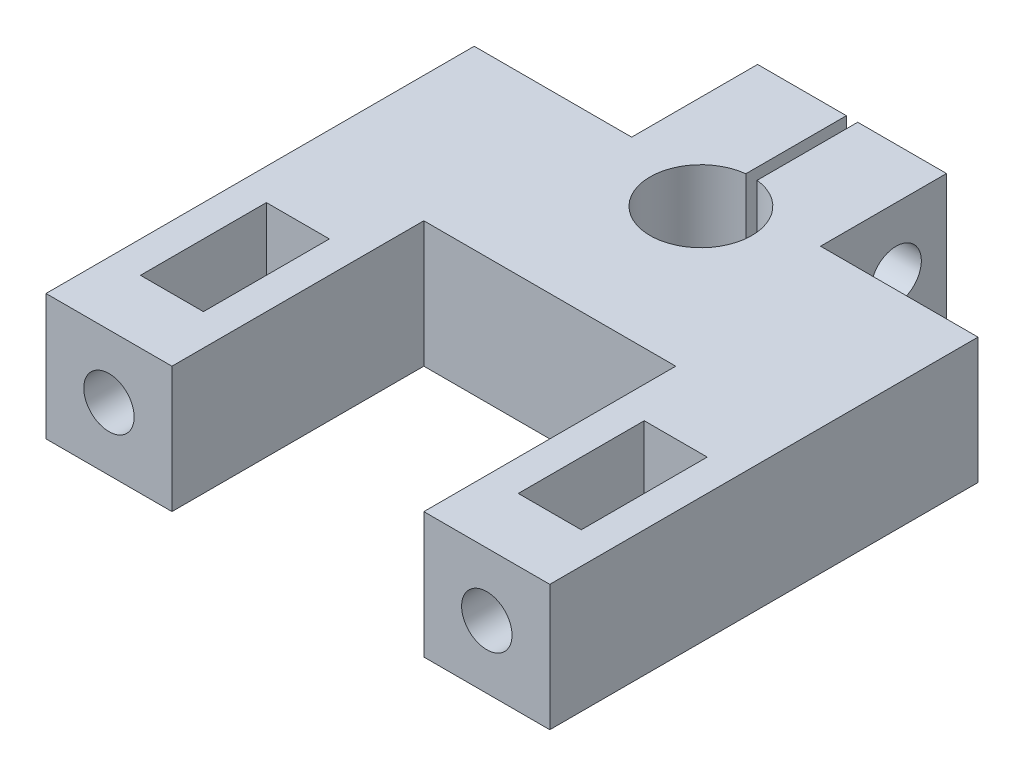
SolidWorks part; units mm, degrees
ref_plane "Front Plane" through (0, 0, 0) normal (0, 0, 1) x (1, 0, 0)
ref_plane "Top Plane" through (0, 0, 0) normal (0, 1, 0) x (1, 0, 0)
ref_plane "Right Plane" through (0, 0, 0) normal (1, 0, 0) x (0, 0, -1)
sketch "Sketch1" plane through (0, 0, 0) normal (0, 1, 0) x (1, 0, 0)
  line L0 (-20, -10) -> (-20, 20)
  line L1 (-20, 20) -> (20, 20)
  line L2 (-10, -10) -> (-10, 10)
  line L3 (-10, 10) -> (10, 10)
  line L4 (10, -10) -> (10, 10)
  line L5 (-10, -10) -> (10, 10) construction
  line L6 (-10, 10) -> (10, -10) construction
  line L7 (20, -10) -> (20, 20)
  line L8 (-20, -10) -> (-10, -10)
  line L9 (10, -10) -> (20, -10)
  point P0 (0, 0)
  dimension "D1" = 20
  dimension "D2" = 10
extrude "Boss-Extrude1" add sketch "Sketch1" along normal blind 10
sketch "Sketch2" plane through (0, 0, 10) normal (0, 0, 1) x (1, 0, 0)
  line L0 (-20, 5) -> (-10, 5) construction
  line L1 (-20, 10) -> (-20, 0) construction
  line L2 (-10, 10) -> (-10, 0) construction
  line L5 (10, 5) -> (20, 5) construction
  line L6 (10, 10) -> (10, 0) construction
  line L7 (20, 10) -> (20, 0) construction
  circle A0 centre (-15, 5) radius 2
  circle A1 centre (15, 5) radius 2
  dimension "D1" = 4
extrude "Cut-Extrude1" cut sketch "Sketch2" against normal blind 15
sketch "Sketch3" plane through (0, 0, -10) normal (0, 0, 1) x (1, 0, 0)
  line L0 (-10, 5) -> (10, 5) construction
  line L1 (-10, 10) -> (-10, 0) construction
  line L2 (10, 10) -> (10, 0) construction
  circle A0 centre (0, 5) radius 2
  dimension "D1" = 4
extrude "Cut-Extrude2" cut sketch "Sketch3" against normal blind 11
sketch "Sketch4" plane through (0, 10, 0) normal (0, 1, 0) x (1, 0, 0)
  line L0 (-20, 20) -> (-20, -10) construction
  line L3 (-20, 10) -> (20, 10)
  line L4 (-20, 10) -> (-20, 34)
  line L5 (-20, 34) -> (20, 34)
  line L6 (20, 10) -> (20, 34)
  line L7 (-10, 10) -> (10, 10) construction
  line L8 (20, -10) -> (20, 20) construction
  dimension "D1" = 24
extrude "Boss-Extrude2" add sketch "Sketch4" against normal through all
sketch "Sketch5" plane through (0, 10, 0) normal (0, 1, 0) x (1, 0, 0)
  line L0 (0, 10) -> (0, 22) construction
  line L1 (-10, 10) -> (10, 10) construction
  circle A0 centre (0, 22) radius 4.04
  dimension "D2" = 8.08
  dimension "D1" = 12
extrude "Cut-Extrude3" cut sketch "Sketch5" against normal through all
sketch "Sketch6" plane through (0, 10, 0) normal (0, 1, 0) x (1, 0, 0)
  line L0 (0, 22) -> (0, 34) construction
  line L1 (20, 34) -> (-20, 34) construction
  line L3 (-0.45, 22) -> (0.45, 22)
  line L4 (-0.45, 22) -> (-0.45, 34)
  line L5 (-0.45, 34) -> (0.45, 34)
  line L6 (0.45, 22) -> (0.45, 34)
  line L7 (-0.45, 22) -> (0.45, 34) construction
  line L8 (-0.45, 34) -> (0.45, 22) construction
  point P5 (0, 28)
  dimension "D1" = 0.9
extrude "Cut-Extrude4" cut sketch "Sketch6" against normal through all
sketch "Sketch8" plane through (-20, 0, 0) normal (-1, 0, 0) x (0, 0, 1)
  line L0 (-34, 5) -> (-30, 5) construction
  line L1 (-34, 0) -> (-34, 10) construction
  circle A0 centre (-30, 5) radius 2
  dimension "D1" = 4
  dimension "D2" = 4
extrude "Cut-Extrude5" cut sketch "Sketch8" against normal blind 40
sketch "Sketch9" plane through (0, 10, 0) normal (0, 1, 0) x (1, 0, 0)
  line L0 (20, 34) -> (0.45, 34) construction
  line L1 (7.5, 34) -> (20, 34)
  line L2 (7.5, 34) -> (7.5, 24)
  line L3 (7.5, 24) -> (20, 24)
  line L4 (20, 34) -> (20, 24)
  line L5 (-7.5, 24) -> (7.5, 24) construction
  line L6 (-20, 34) -> (-7.5, 34)
  line L7 (-20, 34) -> (-20, 24)
  line L8 (-20, 24) -> (-7.5, 24)
  line L9 (-7.5, 34) -> (-7.5, 24)
  point P15 (0, 24)
  dimension "D1" = 15
  dimension "D3" = 10
extrude "Cut-Extrude6" cut sketch "Sketch9" against normal blind 40
sketch "Sketch10" plane through (0, 10, 0) normal (0, 1, 0) x (1, 0, 0)
  line L0 (-15, -10) -> (-15, 24) construction
  line L1 (-20, -10) -> (-10, -10) construction
  line L2 (-20, 24) -> (-7.5, 24) construction
  line L3 (15, -10) -> (15, 24) construction
  line L4 (10, -10) -> (20, -10) construction
  line L5 (7.5, 24) -> (20, 24) construction
  line L6 (-10, -10) -> (-10, 10) construction
  line L7 (-17.5, 5) -> (-12.5, 5)
  line L8 (-17.5, 5) -> (-17.5, -5)
  line L9 (-17.5, -5) -> (-12.5, -5)
  line L10 (-12.5, 5) -> (-12.5, -5)
  line L11 (-17.5, 5) -> (-12.5, -5) construction
  line L12 (-17.5, -5) -> (-12.5, 5) construction
  line L13 (12.5, 5) -> (17.5, 5)
  line L14 (12.5, 5) -> (12.5, -5)
  line L15 (12.5, -5) -> (17.5, -5)
  line L16 (17.5, 5) -> (17.5, -5)
  line L17 (12.5, 5) -> (17.5, -5) construction
  line L18 (12.5, -5) -> (17.5, 5) construction
  line L19 (-15, 0) -> (-10, 0) construction
  point P12 (-15, 0)
  point P17 (15, 0)
  dimension "D1" = 5
  dimension "D2" = 10
extrude "Cut-Extrude7" cut sketch "Sketch10" against normal blind 10
